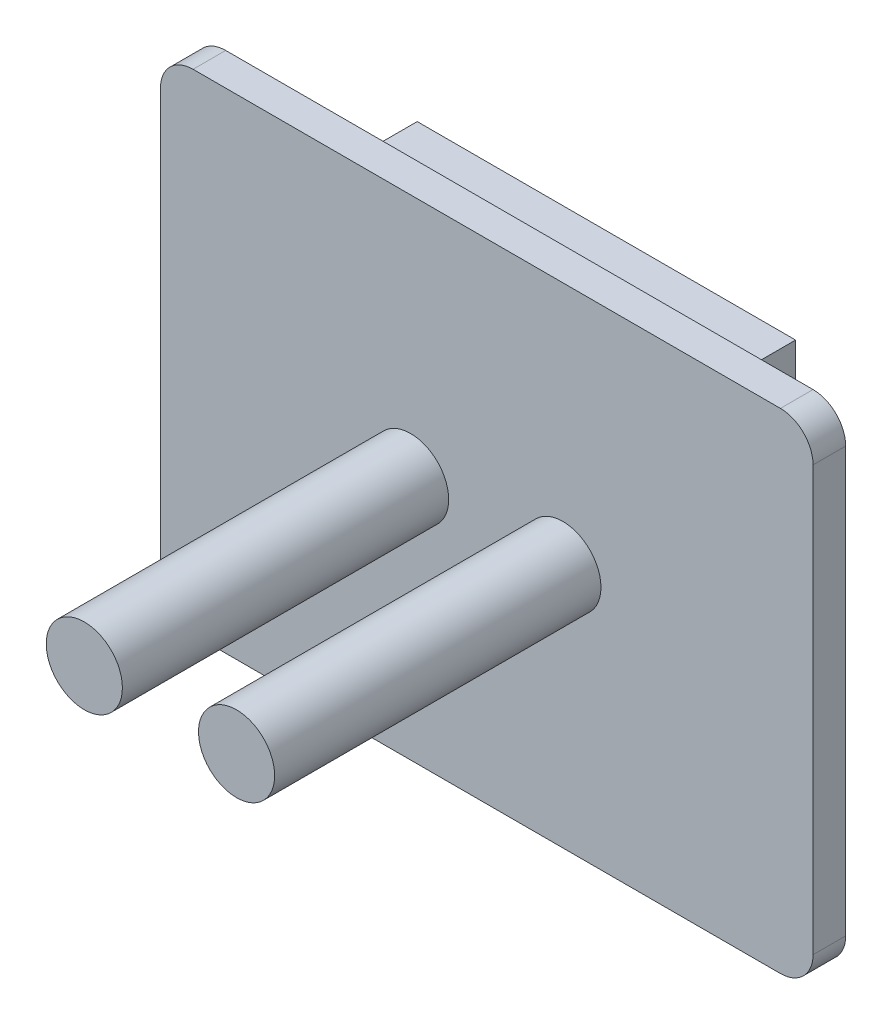
SolidWorks part; units mm, degrees
material "AISI 1035 Steel (SS)"
ref_plane "Front Plane" through (0, 0, 0) normal (0, 0, 1) x (1, 0, 0)
ref_plane "Top Plane" through (0, 0, 0) normal (0, 1, 0) x (1, 0, 0)
ref_plane "Right Plane" through (0, 0, 0) normal (1, 0, 0) x (0, 0, -1)
sketch "Sketch1" plane through (0, 0, 0) normal (0, 0, 1) x (1, 0, 0)
  line L1 (-300, 225) -> (300, 225)
  line L2 (-300, 225) -> (-300, -225)
  line L3 (-300, -225) -> (300, -225)
  line L4 (300, 225) -> (300, -225)
  line L5 (-300, 225) -> (300, -225) construction
  line L6 (-300, -225) -> (300, 225) construction
  point P0 (0, 0)
  dimension "D1" = 600
  dimension "D2" = 450
extrude "Boss-Extrude1" add sketch "Sketch1" along normal blind 30
fillet "Fillet1" radius 30 4 edges at (-300, -225, 15) (300, -225, 15) (300, 225, 15) (-300, 225, 15)
sketch "Sketch2" plane through (0, 0, 0) normal (0, 0, -1) x (-1, 0, 0)
  line L1 (-173.9436, -176.3984) -> (173.9436, -176.3984)
  line L2 (-173.9436, -176.3984) -> (-173.9436, 176.3984)
  line L3 (-173.9436, 176.3984) -> (173.9436, 176.3984)
  line L4 (173.9436, -176.3984) -> (173.9436, 176.3984)
  line L5 (-173.9436, -176.3984) -> (173.9436, 176.3984) construction
  line L6 (-173.9436, 176.3984) -> (173.9436, -176.3984) construction
  point P0 (0, 0)
extrude "Boss-Extrude2" add sketch "Sketch2" along normal blind 80
sketch "Sketch3" plane through (0, 0, 0) normal (0, 1, 0) x (1, 0, 0)
  line L0 (173.9436, 80) -> (300, 0)
rib "Rib2" sketch "Sketch3" sketch "Sketch3" thickness 100 extrusion direction parallel to sketch draft on no parameters "D1"=100
mirror "Mirror1" about plane through (0, 0, 0) normal (1, 0, 0) of "Rib2"
sketch "Sketch4" plane through (0, 0, 30) normal (0, 0, 1) x (1, 0, 0)
  line L0 (0, 0) -> (0, 58.1348) construction
  circle A0 centre (-70, 0) radius 35
  circle A1 centre (70, 0) radius 35
  dimension "D1" = 70
  dimension "D2" = 140
  dimension "D3" = 70
extrude "Boss-Extrude3" add sketch "Sketch4" along normal blind 300
sketch "Sketch5" plane through (0, 0, -80) normal (0, 0, -1) x (-1, 0, 0)
  line L1 (86.6025, 0) -> (43.3013, 75)
  line L2 (43.3013, 75) -> (-43.3013, 75)
  line L3 (-43.3013, 75) -> (-86.6025, 0)
  line L4 (-86.6025, 0) -> (-43.3013, -75)
  line L5 (-43.3013, -75) -> (43.3013, -75)
  line L6 (43.3013, -75) -> (86.6025, 0)
  circle A0 centre (0, 0) radius 75 construction
  dimension "D1" = 150
extrude "Boss-Extrude4" add sketch "Sketch5" along normal blind 60
sketch "Sketch6" plane through (0, 0, 0) normal (0, 0, -1) x (-1, 0, 0)
  line L1 (-230.8864, 176.3984) -> (-242.9739, 197.3346)
  line L2 (-242.9739, 197.3346) -> (-267.149, 197.3346)
  line L3 (-267.149, 197.3346) -> (-279.2365, 176.3984)
  line L4 (-279.2365, 176.3984) -> (-267.149, 155.4622)
  line L5 (-267.149, 155.4622) -> (-242.9739, 155.4622)
  line L6 (-242.9739, 155.4622) -> (-230.8864, 176.3984)
  circle A0 centre (-255.0615, 176.3984) radius 20.9362 construction
extrude "Boss-Extrude5" add sketch "Sketch6" along normal blind 18
mirror "Mirror2" about plane through (0, 0, 0) normal (1, 0, 0) of "Boss-Extrude5"
mirror "Mirror3" about plane through (0, 0, 0) normal (0, 1, 0) of "Mirror2", "Boss-Extrude5"
